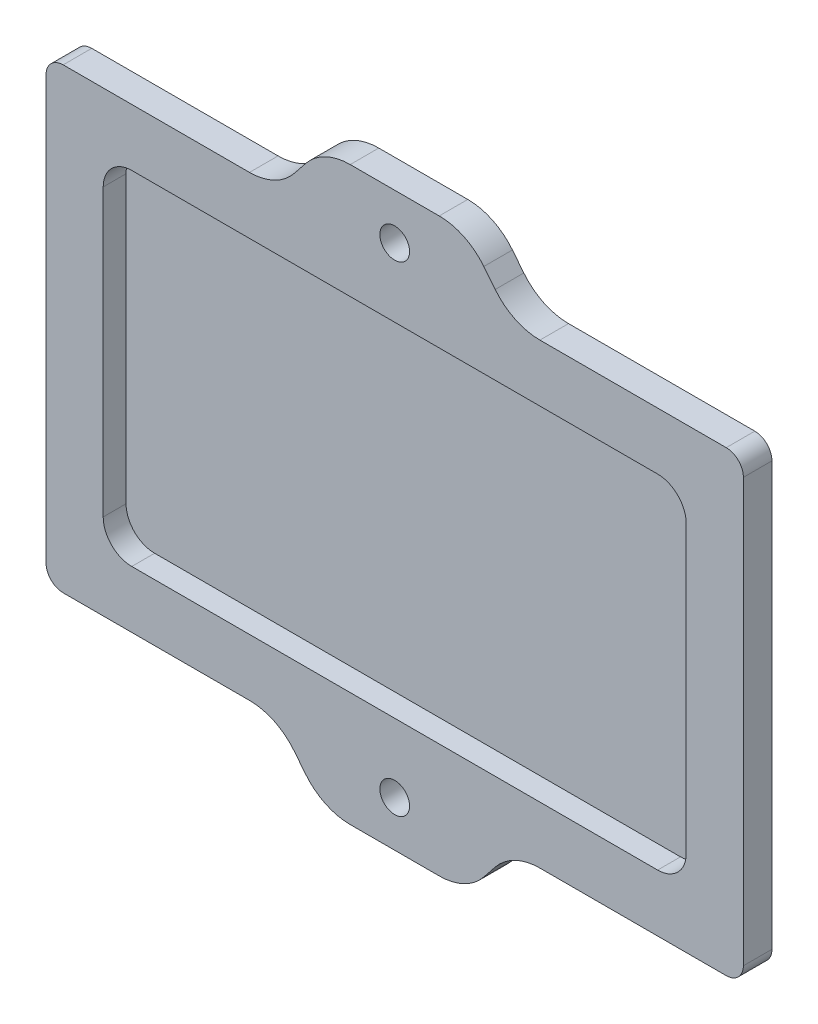
SolidWorks part; units mm, degrees
material "6063-O"
ref_plane "Front Plane" through (0, 0, 0) normal (0, 0, 1) x (1, 0, 0)
ref_plane "Top Plane" through (0, 0, 0) normal (0, 1, 0) x (1, 0, 0)
ref_plane "Right Plane" through (0, 0, 0) normal (1, 0, 0) x (0, 0, -1)
sketch "Sketch1" plane through (0, 0, 0) normal (0, 0, 1) x (1, 0, 0)
  line L0 (-58, 52) -> (58, -52) construction
  line L1 (-58, 55) -> (58, 55)
  line L2 (-61, 52) -> (-61, -52)
  line L3 (-58, -55) -> (58, -55)
  line L4 (61, 52) -> (61, -52)
  line L5 (-58, -52) -> (58, 52) construction
  arc A0 (-61, -52) -> (-58, -55) centre (-58, -52) ccw
  arc A1 (58, -55) -> (61, -52) centre (58, -52) ccw
  arc A2 (61, 52) -> (58, 55) centre (58, 52) ccw
  arc A3 (-61, 52) -> (-58, 55) centre (-58, 52) cw
  point P6 (-61, -55)
  point P11 (61, 55)
  point P14 (-61, 55)
  dimension "D3" = 3
  dimension "D1" = 122
  dimension "D2" = 110
extrude "Boss-Extrude1" add sketch "Sketch1" along normal blind 5
sketch "Sketch3" plane through (0, 0, 5) normal (0, 0, 1) x (1, 0, 0)
  line L0 (-61, 52) -> (-61, -52) construction
  line L2 (58, 55) -> (-58, 55) construction
  line L5 (-58, -55) -> (58, -55) construction
  line L6 (0, 24.2476) -> (0, -7.2931) construction
  line L8 (25.4065, 40) -> (61, 40)
  line L9 (61, -52) -> (61, 52) construction
  line L10 (8.6, 55) -> (17.5979, 43.7529)
  line L11 (8.6, 55) -> (13.4808, 55)
  line L13 (-25.4065, 40) -> (-61, 40)
  line L14 (-8.6, 55) -> (-17.5979, 43.7529)
  line L15 (-57.8903, 0) -> (91.1459, 0) construction
  line L16 (25.4065, -40) -> (61, -40)
  line L17 (8.6, -55) -> (17.5979, -43.7529)
  line L18 (-8.6, -55) -> (-17.5979, -43.7529)
  line L19 (-25.4065, -40) -> (-61, -40)
  line L20 (-61, 40) -> (-61, 59.3739)
  line L21 (-61, 59.3739) -> (-8.6, 59.3739)
  line L22 (-8.6, 59.3739) -> (-8.6, 55)
  line L23 (8.6, 59.3739) -> (8.6, 55)
  line L24 (61, 40) -> (61, 59.3739)
  line L25 (61, 59.3739) -> (8.6, 59.3739)
  line L26 (61, -40) -> (61, -59.3739)
  line L27 (8.6, -59.3739) -> (8.6, -55)
  line L28 (61, -59.3739) -> (8.6, -59.3739)
  line L29 (-61, -40) -> (-61, -59.3739)
  line L30 (-8.6, -59.3739) -> (-8.6, -55)
  line L31 (-61, -59.3739) -> (-8.6, -59.3739)
  circle A0 centre (0, 42) radius 2.6
  circle A1 centre (0, -42) radius 2.6
  arc A2 (25.4065, 40) -> (17.5979, 43.7529) centre (25.4065, 50) cw
  arc A3 (-25.4065, 40) -> (-17.5979, 43.7529) centre (-25.4065, 50) ccw
  arc A4 (25.4065, -40) -> (17.5979, -43.7529) centre (25.4065, -50) ccw
  arc A5 (-25.4065, -40) -> (-17.5979, -43.7529) centre (-25.4065, -50) cw
  arc M1 (-61, -52) -> (-58, -55) centre (-58, -52) ccw
  line M2 (-58, -55) -> (58, -55)
  arc M3 (58, -55) -> (61, -52) centre (58, -52) ccw
  line M4 (61, -52) -> (61, 52)
  arc M5 (61, 52) -> (58, 55) centre (58, 52) ccw
  line M6 (58, 55) -> (-58, 55)
  arc M7 (-58, 55) -> (-61, 52) centre (-58, 52) ccw
  line M8 (-61, 52) -> (-61, -52)
  dimension "D2" = 0
  dimension "D4" = 13
  dimension "D5" = 10
  dimension "D1" = 52.4
  dimension "D6" = 55
  dimension "D7" = 40
extrude "Cut-Extrude1" cut sketch "Sketch3" against normal blind 10 contours L22 L21 L20 M7 M6 | L13 A3 L14 M6 M7 M8 | L24 L25 L23 M6 M5 | A2 L8 L10 M4 M5 M6 | L16 A4 L17 M2 M3 M4 | L28 L26 L27 M3 M2 | A5 L19 L18 M8 M1 M2 | L29 L31 L30 M2 M1 | A1
fillet "Fillet1" radius 10 4 edges at (-8.6, 55, 2.5) (8.6, 55, 2.5) (-8.6, -55, 2.5) (8.6, -55, 2.5)
fillet "Fillet2" radius 3 4 edges at (-61, 40, 2.5) (-61, -40, 2.5) (61, 40, 2.5) (61, -40, 2.5)
sketch "Sketch4" plane through (0, 0, 5) normal (0, 0, 1) x (1, 0, 0)
  line L0 (61, -37) -> (61, 37) construction
  circle A0 centre (0, 42) radius 2.6
  dimension "D1" = 61
  dimension "D2" = 13
  dimension "D3" = 5.2
extrude "Cut-Extrude2" cut sketch "Sketch4" against normal blind 10
sketch "Sketch5" plane through (0, 0, 5) normal (0, 0, 1) x (1, 0, 0)
  line L0 (-61, 37) -> (-61, -37) construction
  line L1 (-46, 30) -> (46, 30)
  line L2 (-51, 25) -> (-51, -25)
  line L3 (-46, -30) -> (46, -30)
  line L4 (51, 25) -> (51, -25)
  line L5 (-25.4065, 40) -> (-58, 40) construction
  line L6 (-25.4065, -40) -> (-58, -40) construction
  line L7 (61, -37) -> (61, 37) construction
  arc A0 (46, 30) -> (51, 25) centre (46, 25) cw
  arc A1 (46, -30) -> (51, -25) centre (46, -25) ccw
  arc A2 (-51, -25) -> (-46, -30) centre (-46, -25) ccw
  arc A3 (-51, 25) -> (-46, 30) centre (-46, 25) cw
  point P10 (51, 0)
  dimension "D5" = 5
  dimension "D1" = 10
  dimension "D2" = 10
  dimension "D3" = 10
  dimension "D4" = 10
extrude "Cut-Extrude3" cut sketch "Sketch5" against normal blind 4
sketch "Sketch6" plane through (0, 0, 0) normal (0, 0, -1) x (-1, 0, 0)
  line L0 (0, 50) -> (-7.7851, 50)
  line L1 (7.7851, 50) -> (-7.7851, 50) construction
  line L2 (-15.5937, 46.2471) -> (-17.5835, 43.7599)
  line L3 (-15.5937, 46.2471) -> (-21.5891, 38.7529) construction
  line L4 (-25.4065, 40) -> (-58, 40) construction
  line L5 (-25.4065, 40) -> (-25.4065, 70)
  line L6 (-25.4065, 70) -> (0, 70)
  line L7 (0, 70) -> (0, 50)
  arc A0 (-7.7851, 50) -> (-15.5937, 46.2471) centre (-7.7851, 40) ccw
  arc A1 (-25.4065, 40) -> (-17.5835, 43.7599) centre (-25.4065, 50.0185) ccw
  dimension "D1" = 20
extrude "Cut-Extrude4" cut sketch "Sketch6" against normal through all
mirror "Mirror1" about plane through (0, 0, 0) normal (1, 0, 0) of "Cut-Extrude4"
mirror "Mirror2" about plane through (0, 0, 0) normal (0, 1, 0) of "Mirror1", "Cut-Extrude4"
